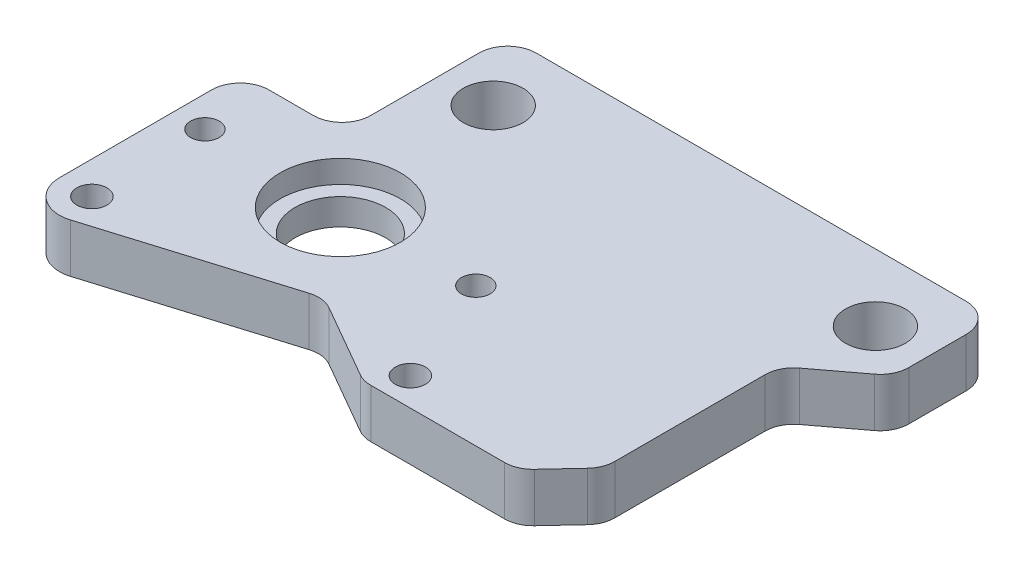
SolidWorks part; units mm, degrees
other "Markup1"
sketch "Sketch6" plane through (-23.3268, 0, -30.7975) normal (-0.0348, 0.9994, -0.0028) x (-0.9993, -0.0348, 0.0153)
sketch "Sketch7" plane through (-23.3268, 0, -30.7975) normal (-0.0348, 0.9994, -0.0028) x (-0.9993, -0.0348, 0.0153)
sketch "Sketch8" plane through (-23.3268, 0, -30.7975) normal (-0.0348, 0.9994, -0.0028) x (-0.9993, -0.0348, 0.0153)
sketch "Sketch10" plane through (-23.3268, 0, -30.7975) normal (-0.0348, 0.9994, -0.0028) x (-0.9993, -0.0348, 0.0153)
sketch "Sketch13" plane through (-23.3268, 0, -30.7975) normal (-0.0348, 0.9994, -0.0028) x (-0.9993, -0.0348, 0.0153)
sketch "Sketch15" plane through (-23.3268, 0, -30.7975) normal (-0.0348, 0.9994, -0.0028) x (-0.9993, -0.0348, 0.0153)
sketch "Sketch16" [suppressed] plane through (-23.3268, 0, -30.7975) normal (-0.0348, 0.9994, -0.0028) x (-0.9993, -0.0348, 0.0153)
sketch "Sketch17" plane through (-23.3268, 0, -30.7975) normal (-0.0348, 0.9994, -0.0028) x (-0.9993, -0.0348, 0.0153)
sketch "Sketch18" plane through (-23.3268, 0, -30.7975) normal (-0.0348, 0.9994, -0.0028) x (-0.9993, -0.0348, 0.0153)
sketch "Sketch19" [suppressed] plane through (-23.3268, 0, -30.7975) normal (-0.0348, 0.9994, -0.0028) x (-0.9993, -0.0348, 0.0153)
sketch "Sketch21" plane through (-23.3268, 0, -30.7975) normal (-0.0348, 0.9994, -0.0028) x (-0.9993, -0.0348, 0.0153)
sketch "Sketch23" plane through (-23.3268, 0, -30.7975) normal (-0.0348, 0.9994, -0.0028) x (-0.9993, -0.0348, 0.0153)
sketch "Sketch24" plane through (-23.3268, 0, -30.7975) normal (-0.0348, 0.9994, -0.0028) x (-0.9993, -0.0348, 0.0153)
sketch "Sketch25" plane through (-23.3268, 0, -30.7975) normal (-0.0348, 0.9994, -0.0028) x (-0.9993, -0.0348, 0.0153)
sketch "Sketch26" [suppressed] plane through (-23.3268, 0, -30.7975) normal (-0.0348, 0.9994, -0.0028) x (-0.9993, -0.0348, 0.0153)
sketch "Sketch27" plane through (-23.3268, 0, -30.7975) normal (-0.0348, 0.9994, -0.0028) x (-0.9993, -0.0348, 0.0153)
sketch "Sketch28" plane through (-23.3268, 0, -30.7975) normal (-0.0348, 0.9994, -0.0028) x (-0.9993, -0.0348, 0.0153)
sketch "Sketch29" plane through (-23.3268, 0, -30.7975) normal (-0.0348, 0.9994, -0.0028) x (-0.9993, -0.0348, 0.0153)
sketch "Sketch30" plane through (-23.3268, 0, -30.7975) normal (-0.0348, 0.9994, -0.0028) x (-0.9993, -0.0348, 0.0153)
sketch "Sketch32" plane through (-23.3268, 0, -30.7975) normal (-0.0348, 0.9994, -0.0028) x (-0.9993, -0.0348, 0.0153)
sketch "Sketch34" [suppressed] plane through (-23.3268, 0, -30.7975) normal (-0.0348, 0.9994, -0.0028) x (-0.9993, -0.0348, 0.0153)
sketch "Sketch35" [suppressed] plane through (-23.3268, 0, -30.7975) normal (-0.0348, 0.9994, -0.0028) x (-0.9993, -0.0348, 0.0153)
sketch "Sketch36" [suppressed] plane through (-23.3268, 0, -30.7975) normal (-0.0348, 0.9994, -0.0028) x (-0.9993, -0.0348, 0.0153)
sketch "Sketch37" plane through (-23.3268, 0, -30.7975) normal (-0.0348, 0.9994, -0.0028) x (-0.9993, -0.0348, 0.0153)
sketch "Sketch38" plane through (-23.3268, 0, -30.7975) normal (-0.0348, 0.9994, -0.0028) x (-0.9993, -0.0348, 0.0153)
sketch "Sketch39" [suppressed] plane through (-23.3268, 0, -30.7975) normal (-0.0348, 0.9994, -0.0028) x (-0.9993, -0.0348, 0.0153)
sketch "Sketch40" plane through (-23.3268, 0, -30.7975) normal (-0.0348, 0.9994, -0.0028) x (-0.9993, -0.0348, 0.0153)
sketch "Sketch41" plane through (-23.3268, 0, -30.7975) normal (-0.0348, 0.9994, -0.0028) x (-0.9993, -0.0348, 0.0153)
sketch "Sketch42" plane through (-23.3268, 0, -30.7975) normal (-0.0348, 0.9994, -0.0028) x (-0.9993, -0.0348, 0.0153)
sketch "Sketch43" plane through (-23.3268, 0, -30.7975) normal (-0.0348, 0.9994, -0.0028) x (-0.9993, -0.0348, 0.0153)
sketch "Sketch44" plane through (-23.3268, 0, -30.7975) normal (-0.0348, 0.9994, -0.0028) x (-0.9993, -0.0348, 0.0153)
sketch "Sketch45" plane through (-23.3268, 0, -30.7975) normal (-0.0348, 0.9994, -0.0028) x (-0.9993, -0.0348, 0.0153)
sketch "Sketch46" plane through (-23.3268, 0, -30.7975) normal (-0.0348, 0.9994, -0.0028) x (-0.9993, -0.0348, 0.0153)
sketch "Sketch47" plane through (-23.3268, 0, -30.7975) normal (-0.0348, 0.9994, -0.0028) x (-0.9993, -0.0348, 0.0153)
sketch "Sketch48" plane through (-23.3268, 0, -30.7975) normal (-0.0348, 0.9994, -0.0028) x (-0.9993, -0.0348, 0.0153)
sketch "Sketch49" plane through (-23.3268, 0, -30.7975) normal (-0.0348, 0.9994, -0.0028) x (-0.9993, -0.0348, 0.0153)
material "6061-T6 (SS)"
ref_plane "X-Y Datum" through (0, 0, 0) normal (0, 0, 1) x (1, 0, 0)
ref_plane "X-Z Datum" through (0, 0, 0) normal (0, 1, 0) x (1, 0, 0)
ref_plane "Y-Z Datum" through (0, 0, 0) normal (1, 0, 0) x (0, 0, -1)
other "Graphic1"
other "Graphic (Closed) -1"
other "Graphic (Closed) -2"
sketch "Sketch2" plane through (0, 0, 0) normal (0, 1, 0) x (1, 0, 0)
  line L0 (48.6426, -18.7325) -> (-23.0162, -18.7325)
  line L1 (24.0125, -14.7036) -> (25.7865, -13.7801) construction
  line L2 (0, 0) -> (105.5557, -202.7707) construction
  line L3 (11.142, -21.4036) -> (-3.5026, -29.027) construction
  line L4 (0, 0) -> (0, -121.3797) construction
  line L5 (-3.5026, -29.027) -> (90.9112, -210.3941) construction
  line L6 (90.9112, -210.3941) -> (105.5557, -202.7707) construction
  line L7 (11.142, -21.4036) -> (24.0125, -14.7036) construction
  line L11 (-12.7, 30.7975) -> (57.15, 30.7975)
  line L12 (57.15, 13.0175) -> (57.15, 30.7975)
  line L13 (57.15, 13.0175) -> (-12.7, 13.0175) construction
  line L15 (44.7685, -18.0975) -> (44.7685, -11.3157) construction
  line L16 (44.7685, -18.0975) -> (34.8625, -18.0975) construction
  line L18 (44.7685, 9.8425) -> (34.8625, 9.8425) construction
  line L20 (44.7685, -11.3157) -> (49.8485, -11.3157) construction
  line L21 (49.8485, -11.3157) -> (49.8485, 3.0607) construction
  line L22 (49.8485, 3.0607) -> (44.7685, 3.0607) construction
  line L23 (44.7685, 3.0607) -> (44.7685, 9.8425) construction
  line L24 (34.8625, -18.0975) -> (34.8625, 9.8425) construction
  line L25 (48.6426, -18.7325) -> (57.15, 13.0175)
  line L26 (-12.7, 30.7975) -> (-12.7, 13.0175)
  line L28 (-12.5603, 0) -> (-16.51, -40.5272) construction
  line L30 (-23.0162, -18.7325) -> (-12.7, 13.0175)
  circle A0 centre (0, 0) radius 3.175
  circle A1 centre (24.0125, -14.7036) radius 2
  circle A2 centre (-1.5875, 21.9075) radius 3.9688
  circle A3 centre (49.2125, 21.9075) radius 3.9687
  circle A4 centre (39.8485, -4.1275) radius 5.1
  circle A5 centre (24.0125, -14.7036) radius 3.175 construction
  circle A6 centre (39.8485, -14.6275) radius 1.6
  circle A7 centre (39.8485, 6.3725) radius 1.6
  circle A8 centre (-17.2047, -14.9225) radius 3.175 construction
  circle A9 centre (-17.2047, -14.9225) radius 2
  point P9 (11.142, -21.4036)
  point P30 (49.8485, -4.1275)
  point P31 (34.8625, -4.1275)
  dimension "D1" = 6.35
  dimension "D8" = 4
  dimension "D10" = 7.9375
  dimension "D11" = 7.9375
  dimension "D16" = 27.94
  dimension "D23" = 10.2
  dimension "D20" = 6.35
  dimension "D30" = 3.2
  dimension "D32" = 3.2
  dimension "D34" = 6.35
  dimension "D35" = 4
  dimension "D3" = 13.0175
  dimension "D4" = 16.51
  dimension "D5" = 228.6
  dimension "D6" = 24.13
  dimension "D7" = 27.5
  dimension "D9" = 16.51
  dimension "D12" = 8.89
  dimension "D13" = 69.85
  dimension "D14" = 7.9375
  dimension "D15" = 31.75
  dimension "D17" = 17.78
  dimension "D18" = 3.175
  dimension "D19" = 14.986
  dimension "D21" = 5.08
  dimension "D22" = 14.3764
  dimension "D24" = 10
  dimension "D25" = 36.83
  dimension "D26" = 50.8
  dimension "D27" = 165
  dimension "D28" = 12.7
  dimension "D29" = 17.3015
  dimension "D31" = 10.5
  dimension "D33" = 10.5
  dimension "D36" = 162
extrude "Boss-Extrude1" [suppressed] add sketch "Sketch2" against normal blind 6.35
ref_point "Point1" [suppressed]
sketch "Sketch3" [suppressed] plane through (0, 0, 0) normal (0, 1, 0) x (1, 0, 0)
  line L0 (39.9681, 6.3725) -> (39.9681, -4.1275) construction
  line L1 (57.2697, 12.9663) -> (-12.5803, 12.9663) construction
  line L5 (39.9681, -4.1275) -> (39.9681, -14.6275) construction
  line L6 (42.0297, -18.7325) -> (20.4164, -18.7325)
  line L7 (57.2697, 12.9663) -> (57.2697, 30.7975)
  line L8 (57.2697, 30.7975) -> (-12.5803, 30.7975)
  line L9 (-12.5803, 30.7975) -> (-12.5803, 12.9663)
  line L10 (40.938, 24.6176) -> (16.9472, 10.7666)
  line L11 (13.3942, 11.8528) -> (6.9035, 25.1608)
  line L12 (8.045, 26.9875) -> (40.303, 26.9875)
  line L13 (57.2697, 12.9663) -> (48.3797, 12.9663)
  line L14 (48.3797, 12.9663) -> (48.3797, -12.3825)
  line L16 (-23.0162, -18.7325) -> (48.6426, -18.7325) construction
  line L18 (16.6064, -14.8627) -> (10.2787, -14.8627)
  line L21 (-8.965, -15.5427) -> (-15.106, -18.7325)
  line L24 (-21.1701, -13.6017) -> (-12.5803, 12.9663)
  line L29 (17.8764, -16.1925) -> (17.8764, -16.1327)
  circle A0 centre (0.1197, 0) radius 3.175
  circle A1 centre (-1.4678, 21.9075) radius 3.9688
  circle A2 centre (49.3322, 21.9075) radius 3.9687
  circle A3 centre (39.9681, -4.1275) radius 5.1
  circle A4 centre (39.9681, -14.6275) radius 1.6
  circle A5 centre (39.9681, 6.3725) radius 1.6
  circle A6 centre (24.1322, -14.7036) radius 2
  circle A7 centre (-17.085, -14.9225) radius 2
  arc A8 (13.3942, 11.8528) -> (16.9472, 10.7666) centre (15.6772, 12.9663) ccw
  arc A9 (8.045, 26.9875) -> (6.9035, 25.1608) centre (8.045, 25.7175) ccw
  arc A10 (40.938, 24.6176) -> (40.303, 26.9875) centre (40.303, 25.7175) ccw
  arc A11 (10.2787, -14.8627) -> (-8.965, -15.5427) centre (0.1197, 0) cw
  arc A12 (-15.106, -18.7325) -> (-21.1701, -13.6017) centre (-17.085, -14.9225) cw
  arc A13 (42.0297, -18.7325) -> (48.3797, -12.3825) centre (42.0297, -12.3825) ccw
  arc A14 (20.4164, -18.7325) -> (17.8764, -16.1925) centre (20.4164, -16.1925) cw
  arc A15 (16.6064, -14.8627) -> (17.8764, -16.1327) centre (16.6064, -16.1327) cw
  dimension "D1" = 6.35
  dimension "D4" = 7.9375
  dimension "D9" = 10.2
  dimension "D10" = 3.2
  dimension "D11" = 4
  dimension "D21" = 2.54
  dimension "D22" = 1.27
  dimension "D3" = 6.35
  dimension "D28" = 2.54
  dimension "D29" = 1.27
  dimension "D2" = 7.9375
  dimension "D5" = 50.8
  dimension "D6" = 21.9075
  dimension "D7" = 1.5875
  dimension "D8" = 8.89
  dimension "D12" = 10.5
  dimension "D13" = 17.2047
  dimension "D14" = 24.0125
  dimension "D15" = 14.7036
  dimension "D16" = 39.8485
  dimension "D17" = 4.1275
  dimension "D18" = 14.9225
  dimension "D19" = 69.85
  dimension "D20" = 3.81
  dimension "D23" = 30
  dimension "D24" = 64
  dimension "D25" = 32.258
  dimension "D26" = 15.5575
  dimension "D27" = 25.3488
  dimension "D30" = 8.89
sketch "Sketch4" plane through (0, 0, 0) normal (0, 1, 0) x (1, 0, 0)
  line L0 (39.8485, 6.3725) -> (39.8485, -4.1275) construction
  line L1 (56.1975, 13.0175) -> (-8.5725, 13.0175) construction
  line L2 (39.8485, -4.1275) -> (39.8485, -14.6275) construction
  line L3 (40.2577, -18.4375) -> (22.4839, -18.4375)
  line L5 (52.3875, 30.7975) -> (-4.7625, 30.7975)
  line L6 (-8.5725, 26.9875) -> (-8.5725, 12.6075)
  line L40 (47.4685, 8.9851) -> (47.4685, -10.9806)
  line L41 (46.4449, -13.579) -> (43.0442, -17.2259)
  line L43 (48.9856, 12.0279) -> (54.6804, 16.3193)
  line L44 (56.1975, 19.3621) -> (56.1975, 26.9875)
  line L50 (-17.78, -15.24) -> (0, 0) construction
  line L58 (20.5837, -17.9298) -> (10.7795, -12.2883)
  line L59 (0, 0) -> (0, 5.6144) construction
  line L60 (7.7656, -11.947) -> (-16.5178, -19.3694)
  line L61 (-22.098, -15.24) -> (-22.098, 4.9875)
  line L62 (-18.288, 8.7975) -> (-12.3825, 8.7975)
  circle A0 centre (0, 0) radius 8
  circle A1 centre (-1.5875, 21.9075) radius 3.9688
  circle A2 centre (49.2125, 21.9075) radius 3.9687
  circle A6 centre (24.0125, -14.7036) radius 2
  circle A7 centre (-17.78, -15.24) radius 2
  arc A12 (-16.5178, -19.3694) -> (-22.098, -15.24) centre (-17.78, -15.24) cw
  arc A19 (-8.5725, 26.9875) -> (-4.7625, 30.7975) centre (-4.7625, 26.9875) cw
  arc A20 (52.3875, 30.7975) -> (56.1975, 26.9875) centre (52.3875, 26.9875) cw
  circle A33 centre (24.0125, -14.7036) radius 3.5 construction
  arc A45 (56.1975, 19.3621) -> (54.6804, 16.3193) centre (52.3875, 19.3621) cw
  arc A46 (47.4685, 8.9851) -> (48.9856, 12.0279) centre (51.2785, 8.9851) cw
  arc A47 (47.4685, -10.9806) -> (46.4449, -13.579) centre (43.6585, -10.9806) cw
  arc A48 (43.0442, -17.2259) -> (40.2577, -18.4375) centre (40.2577, -14.6275) cw
  arc A51 (-22.098, 4.9875) -> (-18.288, 8.7975) centre (-18.288, 4.9875) cw
  arc A52 (-12.3825, 8.7975) -> (-8.5725, 12.6075) centre (-12.3825, 12.6075) ccw
  arc A53 (22.4839, -18.4375) -> (20.5837, -17.9298) centre (22.4839, -14.6275) cw
  arc A54 (7.7656, -11.947) -> (10.7795, -12.2883) centre (8.8793, -15.5906) cw
  circle A55 centre (0, 0) radius 18 construction
  circle A57 centre (18, 0) radius 1.8986
  circle A58 centre (-18, 0) radius 1.8986
  point P30 (21.466, -18.4375)
  point P36 (9.3466, -11.4637)
  point P58 (-8.5725, 30.7975)
  point P77 (56.1975, 17.4625)
  point P84 (41.9143, -18.4375)
  dimension "D1" = 16
  dimension "D2" = 7.9375
  dimension "D7" = 22
  dimension "D8" = 4
  dimension "D19" = 3.81
  dimension "D20" = 6.9738
  dimension "D25" = 3.81
  dimension "D26" = 7
  dimension "D27" = 25.8644
  dimension "D31" = 3.7973
  dimension "D33" = 4.318
  dimension "D23" = 3.81
  dimension "D45" = 3.81
  dimension "D18" = 3.81
  dimension "D29" = 3.81
  dimension "D30" = 36
  dimension "D3" = 50.8
  dimension "D4" = 21.9075
  dimension "D5" = 1.5875
  dimension "D9" = 10.5
  dimension "D10" = 24.0125
  dimension "D11" = 14.7036
  dimension "D12" = 39.8485
  dimension "D13" = 4.1275
  dimension "D14" = 15.24
  dimension "D15" = 17.78
  dimension "D16" = 6.985
  dimension "D17" = 8.89
  dimension "D21" = 17.78
  dimension "D22" = 12.1194
  dimension "D24" = 7.62
  dimension "D28" = 4.9865
  dimension "D36" = 9.525
  dimension "D40" = 127
  dimension "D43" = 137
  dimension "D60" = 6.985
extrude "Boss-Extrude2" add sketch "Sketch4" against normal blind 6.5
ref_point "Point2"
ref_point "Point3"
ref_point "Point4"
sketch "Sketch31" plane through (0, -6.5, 0) normal (0, -1, 0) x (1, 0, 0)
  circle A0 centre (0, 0) radius 6.025
  circle A1 centre (0, 0) radius 8
  dimension "D1" = 12.05
  dimension "D2" = 16
extrude "Boss-Extrude5" add sketch "Sketch31" against normal blind 3.5
sketch "Sketch33" [suppressed] plane through (0, 0, 0) normal (0, 1, 0) x (1, 0, 0)
  circle A0 centre (0, 0) radius 8
  circle A1 centre (0, 0) radius 6.025
  dimension "D1" = 12.05
  dimension "D2" = 16
extrude "Boss-Extrude6" [suppressed] add sketch "Sketch33" against normal blind 3.5
